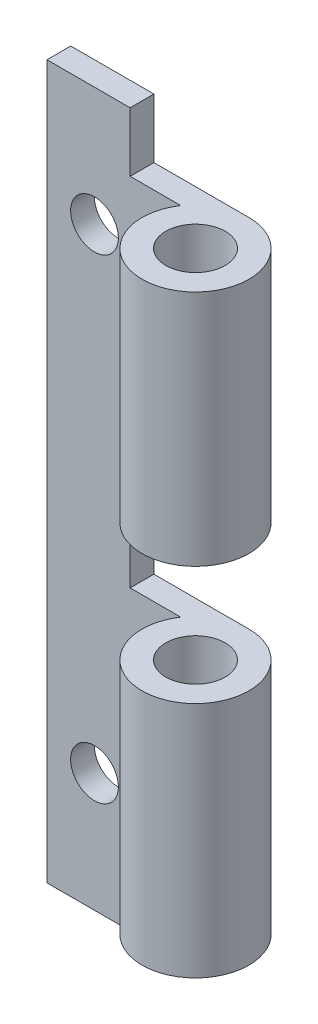
SolidWorks part; units mm, degrees
ref_plane "Front" through (0, 0, 0) normal (0, 0, 1) x (1, 0, 0)
ref_plane "Top" through (0, 0, 0) normal (0, 1, 0) x (1, 0, 0)
ref_plane "Right" through (0, 0, 0) normal (1, 0, 0) x (0, 0, -1)
sketch "Sketch1" plane through (0, 0, 0) normal (0, 0, 1) x (1, 0, 0)
  line L1 (0, 0) -> (-19.05, 0)
  line L2 (0, 0) -> (0, 76.2)
  line L3 (0, 76.2) -> (-19.05, 76.2)
  line L4 (-19.05, 0) -> (-19.05, 76.2)
  dimension "D1" = 19.05
  dimension "D2" = 76.2
extrude "Boss-Extrude1" add sketch "Sketch1" along normal blind 2.54
sketch "Sketch2" plane through (0, 0, 0) normal (0, -1, 0) x (-1, 0, 0)
  line L0 (19.05, 0) -> (0, 0) construction
  circle A0 centre (0, -5.715) radius 5.715
  circle A1 centre (0, -5.715) radius 3.175
  point P6 (0, -8.366)
  dimension "D1" = 2.54
  dimension "D2" = 6.35
extrude "Boss-Extrude2" add sketch "Sketch2" against normal up to surface (76.2 mm away) up to face at (-9.525, 76.2, 1.27)
sketch "Sketch3" plane through (0, 0, 0) normal (0, 0, -1) x (-1, 0, 0)
  line L0 (0, 0) -> (0, 76.2) construction
  line L1 (10.16, 6.35) -> (-15.24, 6.35)
  line L2 (10.16, 6.35) -> (10.16, 0)
  line L3 (10.16, 0) -> (-15.24, 0)
  line L4 (-15.24, 6.35) -> (-15.24, 0)
  line L5 (10.16, 69.85) -> (-15.24, 69.85)
  line L6 (10.16, 69.85) -> (10.16, 76.2)
  line L7 (10.16, 76.2) -> (-15.24, 76.2)
  line L8 (-15.24, 69.85) -> (-15.24, 76.2)
  line L9 (10.16, 31.75) -> (-15.24, 31.75)
  line L10 (10.16, 31.75) -> (10.16, 44.45)
  line L11 (10.16, 44.45) -> (-15.24, 44.45)
  line L12 (-15.24, 31.75) -> (-15.24, 44.45)
  line L13 (0, 76.2) -> (19.05, 76.2) construction
  line L14 (19.05, 0) -> (0, 0) construction
  line L16 (19.05, 76.2) -> (19.05, 0) construction
  point P18 (10.16, 38.1)
  point P20 (19.05, 38.1)
  dimension "D1" = 12.7
  dimension "D2" = 6.35
  dimension "D3" = 10.16
  dimension "D4" = 25.4
  dimension "D5" = 25.4
  dimension "D6" = 6.35
  dimension "D7" = 10.16
  dimension "D8" = 25.4
  dimension "D9" = 10.16
extrude "Cut-Extrude1" cut sketch "Sketch3" against normal through all
hole_wizard "#10 Clearance Hole1" positions "Sketch4" profile "Sketch5" hole size "#10" standard "ANSI Inch"
sketch "Sketch4" plane through (0, 0, 2.54) normal (0, 0, 1) x (1, 0, 0)
  line L0 (-10.16, 76.2) -> (-19.05, 76.2) construction
  line L1 (-19.05, 0) -> (-10.16, 0) construction
  line L3 (-19.05, 76.2) -> (-19.05, 0) construction
  point P0 (-13.97, 63.5)
  point P2 (-13.97, 12.7)
  point P5 (0, 0)
  point P14 (-19.05, 16.0964)
  point P17 (0, 0)
  dimension "D1" = 12.7
  dimension "D2" = 12.7
  dimension "D3" = 5.08
sketch "Sketch5" plane through (-13.97, 63.5, 2.54) normal (1, 0, 0) x (0, -1, 0)
  line L0 (0, 0) -> (0, 4.0728)
  line L1 (0, 4.0728) -> (2.5527, 2.539)
  line L2 (2.5527, 2.539) -> (2.5527, 0)
  line L5 (2.5527, 0) -> (0, 0)
  line L10 (0, 4.0728) -> (-2.5527, 2.539) construction
  line L11 (0, -6.35) -> (0, 107.95) construction
  dimension "Hole Dia." = 5.1054
  dimension "Hole Depth" = 2.539
  dimension "Drill Angle" = 118
sketch "Sketch6" plane through (0, 0, 0) normal (0, 0, -1) x (-1, 0, 0)
  line L0 (5.08, 69.85) -> (5.08, 44.45) construction
  line L1 (0, 69.85) -> (10.16, 69.85) construction
  line L2 (10.16, 44.45) -> (0, 44.45) construction
  line L3 (0, 44.45) -> (0, 69.85) construction
  dimension "D1" = 5.08
